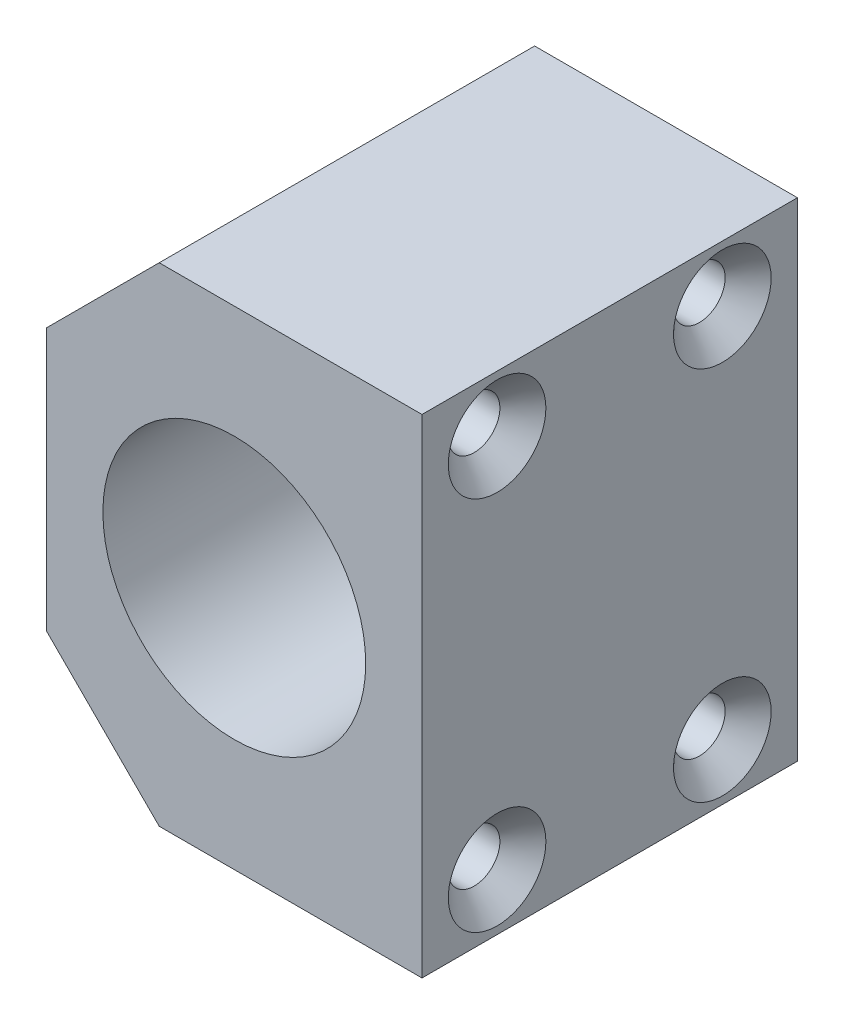
SolidWorks part; units mm, degrees
ref_plane "Front Plane" through (0, 0, 0) normal (0, 0, 1) x (1, 0, 0)
ref_plane "Top Plane" through (0, 0, 0) normal (0, 1, 0) x (1, 0, 0)
ref_plane "Right Plane" through (0, 0, 0) normal (1, 0, 0) x (0, 0, -1)
sketch "Sketch1" plane through (0, 0, 0) normal (0, 0, 1) x (1, 0, 0)
  line L0 (-20, -14) -> (-8, -26)
  line L1 (-8, 26) -> (20, 26)
  line L2 (-20, 14) -> (-20, -14)
  line L3 (-8, -26) -> (20, -26)
  line L4 (20, 26) -> (20, -26)
  line L5 (-20, 26) -> (20, -26) construction
  line L6 (-20, -26) -> (20, 26) construction
  line L7 (-8, 26) -> (-20, 14)
  point P0 (0, 0)
  dimension "D1" = 52
  dimension "D2" = 40
extrude "Boss-Extrude1" add sketch "Sketch1" along normal blind 40
sketch "Sketch2" plane through (0, 0, 40) normal (0, 0, 1) x (1, 0, 0)
  circle A0 centre (0, 0) radius 14
  dimension "D1" = 28
extrude "Cut-Extrude1" cut sketch "Sketch2" against normal blind 40
hole_wizard "CSK for M5 Countersunk Raised Head Screw1" positions "Sketch4" profile "Sketch3" countersink size "M5" standard "ISO"
sketch "Sketch4" plane through (20, 0, 0) normal (1, 0, 0) x (0, 0, -1)
  line L0 (0, -26) -> (0, 26) construction
  line L1 (-40, -26) -> (-40, 26) construction
  point P0 (-32, 20)
  point P2 (-8, 20)
  point P4 (-8, -20)
  point P6 (-32, -20)
  point P9 (0, 0)
  dimension "D1" = 24
  dimension "D2" = 24
  dimension "D3" = 40
  dimension "D4" = 20
  dimension "D5" = 8
  dimension "D6" = 8
sketch "Sketch3" plane through (20, 20, 32) normal (0, 1, 0) x (0, 0, -1)
  line L0 (0, 0) -> (0, 13.6524)
  line L1 (0, 13.6524) -> (2.75, 12)
  line L2 (2.75, 12) -> (2.75, 2.45)
  line L3 (2.75, 2.45) -> (5.2, 0)
  line L5 (5.2, 0) -> (0, 0)
  line L6 (-2.75, 2.45) -> (-5.2, 0) construction
  line L10 (0, 13.6524) -> (-2.75, 12) construction
  line L11 (0, -6.35) -> (0, 107.95) construction
  dimension "Hole Dia." = 5.5
  dimension "Hole Depth" = 12
  dimension "Near C'Sink Dia." = 10.4
  dimension "Near C'Sink Angle" = 90
  dimension "Drill Angle" = 118
